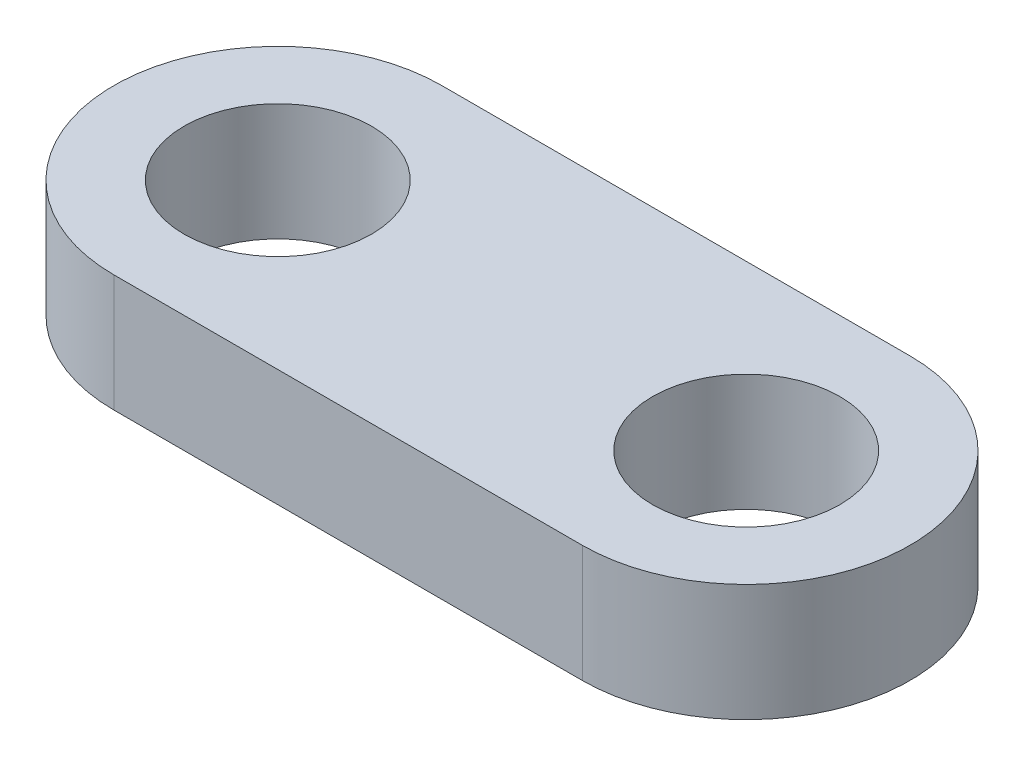
SolidWorks part; units mm, degrees
ref_plane "Front Plane" through (0, 0, 0) normal (0, 0, 1) x (1, 0, 0)
ref_plane "Top Plane" through (0, 0, 0) normal (0, 1, 0) x (1, 0, 0)
ref_plane "Right Plane" through (0, 0, 0) normal (1, 0, 0) x (0, 0, -1)
sketch "Sketch1" plane through (0, 0, 0) normal (0, 1, 0) x (1, 0, 0)
  line L0 (0, 0) -> (20, 0) construction
  line L1 (0, 7) -> (20, 7)
  line L2 (0, -7) -> (20, -7)
  arc A0 (0, 7) -> (0, -7) centre (0, 0) ccw
  arc A1 (20, -7) -> (20, 7) centre (20, 0) ccw
  circle A2 centre (0, 0) radius 4
  circle A3 centre (20, 0) radius 4
  point P3 (10, 0)
  dimension "D2" = 7
  dimension "D3" = 8
  dimension "D1" = 20
extrude "Boss-Extrude1" add sketch "Sketch1" along normal mid plane 5
